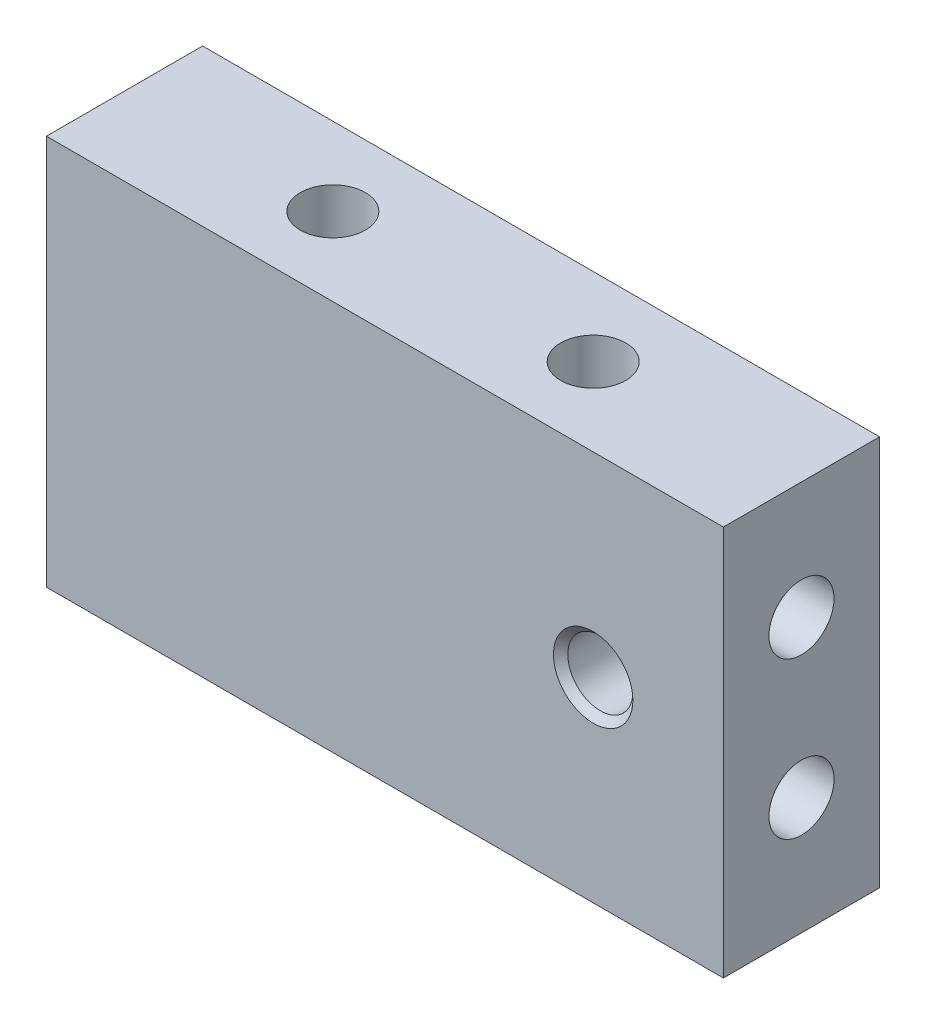
SolidWorks part; units mm, degrees
material "6063-T1"
ref_plane "前视基准面" through (0, 0, 0) normal (0, 0, 1) x (1, 0, 0)
ref_plane "上视基准面" through (0, 0, 0) normal (0, 1, 0) x (1, 0, 0)
ref_plane "右视基准面" through (0, 0, 0) normal (1, 0, 0) x (0, 0, -1)
sketch "草图1" plane through (0, 0, 0) normal (0, 0, 1) x (1, 0, 0)
  line L0 (0, 10.6463) -> (0, -8.7034) construction
  line L2 (-13, -7.5) -> (13, -7.5)
  line L3 (-13, -7.5) -> (-13, 7.5)
  line L4 (-13, 7.5) -> (13, 7.5)
  line L5 (13, -7.5) -> (13, 7.5)
  line L6 (-13, -7.5) -> (13, 7.5) construction
  line L7 (-13, 7.5) -> (13, -7.5) construction
  point P3 (0, 0)
  dimension "D1" = 26
  dimension "D2" = 15
extrude "凸台-拉伸1" add sketch "草图1" along normal blind 5
sketch "草图2" plane through (0, 0, 5) normal (0, 0, 1) x (1, 0, 0)
  line L0 (0, 11.4812) -> (0, -11.5028) construction
  line L5 (13, -7.5) -> (13, 7.5)
  line L6 (13, 7.5) -> (-13, 7.5)
  line L7 (-13, 7.5) -> (-13, -7.5)
  line L8 (-13, -7.5) -> (13, -7.5)
  line L9 (13, -7.5) -> (13, 7.5)
  line L10 (13, 7.5) -> (-13, 7.5)
  line L11 (-13, 7.5) -> (-13, -7.5)
  line L12 (-13, -7.5) -> (13, -7.5)
  dimension "D1" = 0
extrude "凸台-拉伸2" add sketch "草图2" along normal blind 1
sketch "草图3" plane through (-13, 0, 0) normal (-1, 0, 0) x (0, 0, 1)
  line L0 (8.9091, 0) -> (-5.7088, 0) construction
  line L1 (3, 10.2021) -> (3, -13.0987) construction
  line L2 (0, 7.5) -> (0, -7.5) construction
  circle A0 centre (3, 3) radius 1.5
  circle A2 centre (3, -3) radius 1.5
  dimension "D1" = 3
  dimension "D4" = 3
  dimension "D2" = 3
  dimension "D3" = 3
hole_wizard "M3 螺纹孔1" positions "3D草图1" profile "草图4" tap size "M3" standard "GB"
sketch3d "3D草图1"
  point P0 (-13, -3, 3)
  point P6 (-13, 3, 3)
sketch "草图4" plane through (-13, -3, 3) normal (0, 1, 0) x (0, 0, 1)
  line L0 (0, 0) -> (0, 5.7511)
  line L1 (0, 5.7511) -> (1.25, 5)
  line L2 (1.25, 5) -> (1.25, 0)
  line L5 (1.25, 0) -> (0, 0)
  line L10 (0, 5.7511) -> (-1.25, 5) construction
  line L11 (0, -6.35) -> (0, 107.95) construction
  dimension "螺纹孔钻头直径" = 2.5
  dimension "螺纹孔钻头深度" = 5
  dimension "导头角度" = 118
cosmetic thread "孔螺蚊线1" parameters "D1"=4.5, "D2"=3
cosmetic thread "孔螺蚊线3" parameters "D1"=4.5, "D2"=3
mirror "镜向1" about plane through (0, 0, 0) normal (1, 0, 0) of "M3 螺纹孔1"
sketch "草图6" plane through (0, 7.5, 0) normal (0, 1, 0) x (1, 0, 0)
  line L0 (-15.2106, -3) -> (17.3898, -3) construction
  line L1 (13, 0) -> (-13, 0) construction
  line L2 (0, -12.3796) -> (0, 4.4836) construction
  circle A0 centre (-5, -3) radius 1.5
  circle A1 centre (5, -3) radius 1.5
  dimension "D2" = 5
  dimension "D3" = 5
  dimension "D4" = 3
  dimension "D1" = 3
hole_wizard "M3 螺纹孔2" positions "3D草图3" profile "草图7" tap size "M3" standard "GB"
sketch3d "3D草图3"
  point P0 (-5, 7.5, 3)
  point P3 (5, 7.5, 3)
sketch "草图7" plane through (-5, 7.5, 3) normal (1, 0, 0) x (0, 0, 1)
  line L0 (0, 0) -> (0, 7.7511)
  line L1 (0, 7.7511) -> (1.25, 7)
  line L2 (1.25, 7) -> (1.25, 0)
  line L5 (1.25, 0) -> (0, 0)
  line L10 (0, 7.7511) -> (-1.25, 7) construction
  line L11 (0, -6.35) -> (0, 107.95) construction
  dimension "螺纹孔钻头直径" = 2.5
  dimension "螺纹孔钻头深度" = 7
  dimension "导头角度" = 118
cosmetic thread "孔螺蚊线4" parameters "D1"=4.5, "D2"=3
cosmetic thread "孔螺蚊线5" parameters "D1"=4.5, "D2"=3
hole_wizard "M3 螺纹孔3" positions "草图8" profile "草图9" tap size "M3" standard "GB" end condition through all
sketch "草图8" plane through (0, 0, 6) normal (0, 0, 1) x (1, 0, 0)
  line L0 (8, 0) -> (13, 0) construction
  line L1 (13, -7.5) -> (13, 7.5) construction
  point P0 (8, 0)
  dimension "D1" = 5
sketch "草图9" plane through (8, 0, 6) normal (1, 0, 0) x (0, -1, 0)
  line L0 (0, 0) -> (0, 6)
  line L1 (0, 6) -> (1.25, 6)
  line L2 (1.25, 6) -> (1.25, 0.275)
  line L3 (1.25, 0.275) -> (1.525, 0)
  line L5 (1.525, 0) -> (0, 0)
  line L6 (-1.25, 0.275) -> (-1.525, 0) construction
  line L11 (0, -6.35) -> (0, 107.95) construction
  dimension "通孔螺纹孔钻头直径" = 2.5
  dimension "通孔螺纹孔钻头深度" = 6
  dimension "近端锥形沉头孔直径" = 3.05
  dimension "近端锥形沉头孔角度" = 90
cosmetic thread "孔螺蚊线6" parameters "D2"=3
